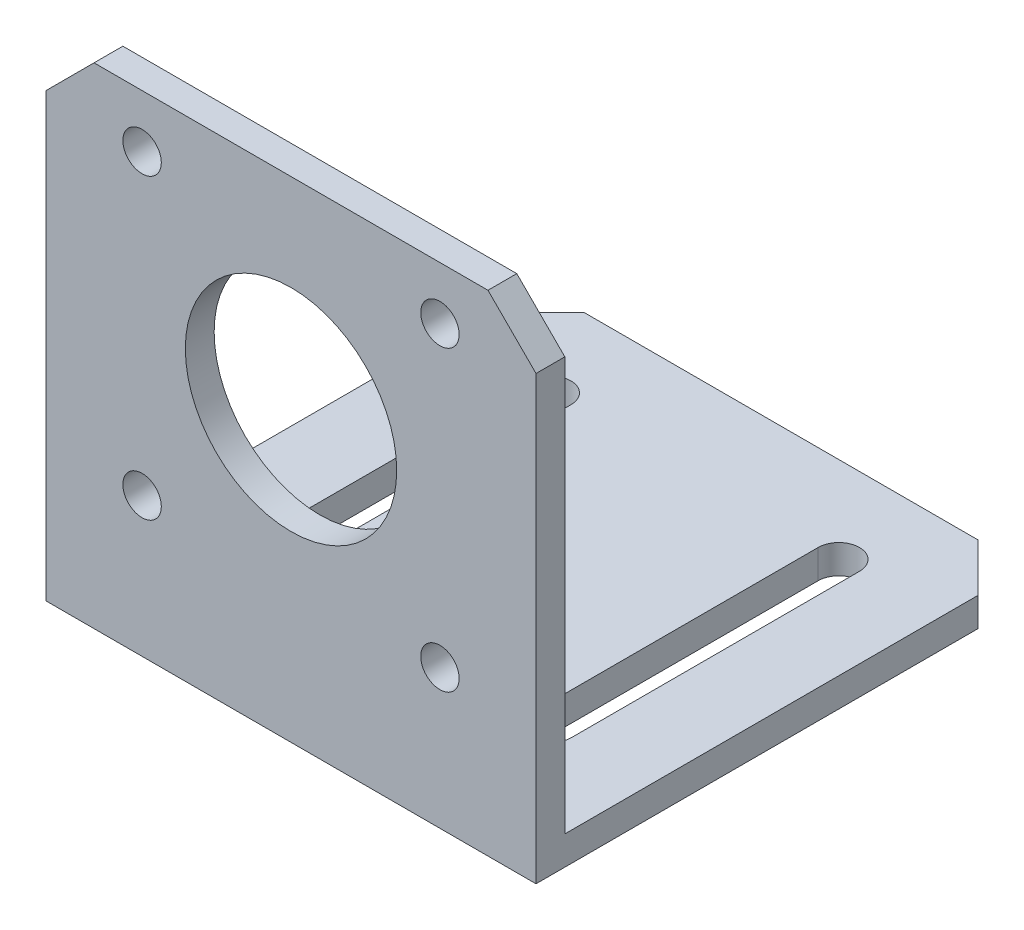
SolidWorks part; units mm, degrees
ref_plane "Ön Düzlem" through (0, 0, 0) normal (0, 0, 1) x (1, 0, 0)
ref_plane "Üst Düzlem" through (0, 0, 0) normal (0, 1, 0) x (1, 0, 0)
ref_plane "Sağ Düzlem" through (0, 0, 0) normal (1, 0, 0) x (0, 0, -1)
sketch "Çizim1" plane through (0, 0, 0) normal (0, 0, 1) x (1, 0, 0)
  line L1 (25.5, -25.5) -> (-25.5, -25.5)
  line L2 (25.5, -25.5) -> (25.5, 25.5)
  line L3 (25.5, 25.5) -> (-25.5, 25.5)
  line L4 (-25.5, -25.5) -> (-25.5, 25.5)
  line L5 (25.5, -25.5) -> (-25.5, 25.5) construction
  line L6 (25.5, 25.5) -> (-25.5, -25.5) construction
  point P0 (0, 0)
  dimension "D1" = 51
  dimension "D2" = 51
extrude "Yükseklik-Ekstrüzyon1" add sketch "Çizim1" along normal blind 51
sketch "Çizim2" plane through (-25.5, 0, 0) normal (-1, 0, 0) x (0, 0, 1)
  line L0 (51, 25.5) -> (51, -25.5) construction
  line L1 (-6.245, 30.9262) -> (48, 30.9262)
  line L2 (-6.245, 30.9262) -> (-6.245, -22.5)
  line L3 (-6.245, -22.5) -> (48, -22.5)
  line L4 (48, 30.9262) -> (48, -22.5)
  line L5 (-6.245, 30.9262) -> (48, -22.5) construction
  line L6 (-6.245, -22.5) -> (48, 30.9262) construction
  line L7 (51, -25.5) -> (0, -25.5) construction
  point P0 (20.8775, 4.2131)
  dimension "D1" = 3
  dimension "D2" = 3
extrude "Kes-Ekstrüzyon1" cut sketch "Çizim2" against normal blind 51
sketch "Çizim3" plane through (0, 0, 51) normal (0, 0, 1) x (1, 0, 0)
  line L0 (25.5, 25.5) -> (-25.5, 25.5) construction
  line L1 (13.432, 4.5) -> (-24.1651, 4.5) construction
  line L2 (0, 20.785) -> (0, -17.5241) construction
  circle A0 centre (0, 4.5) radius 11
  circle A1 centre (-15.5, 20) radius 2
  circle A2 centre (15.5, 20) radius 2
  circle A3 centre (-15.5, -11) radius 2
  circle A4 centre (15.5, -11) radius 2
  dimension "D1" = 22
  dimension "D3" = 4
  dimension "D2" = 21
  dimension "D4" = 31
  dimension "D5" = 31
extrude "Kes-Ekstrüzyon2" cut sketch "Çizim3" against normal blind 51
chamfer "Pah1" distance 5 angle 45 1 edges at (-25.5, 25.5, 49.5)
chamfer "Pah2" distance 5 angle 45 3 edges at (25.5, -24, 0) (-25.5, -24, 0) (25.5, 25.5, 49.5)
sketch "Çizim4" plane through (0, -25.5, 0) normal (0, -1, 0) x (1, 0, 0)
  line L0 (-15.015, 39) -> (-15.015, 9) construction
  line L1 (-12.865, 39) -> (-12.865, 9)
  line L2 (-17.165, 39) -> (-17.165, 9)
  line L3 (0, -2.7893) -> (0, 57.8306) construction
  line L4 (15.015, 39) -> (15.015, 9) construction
  line L5 (12.865, 39) -> (12.865, 9)
  line L6 (17.165, 39) -> (17.165, 9)
  line L7 (-20.5, 0) -> (20.5, 0) construction
  arc A0 (-12.865, 39) -> (-17.165, 39) centre (-15.015, 39) ccw
  arc A1 (-17.165, 9) -> (-12.865, 9) centre (-15.015, 9) ccw
  arc A2 (12.865, 39) -> (17.165, 39) centre (15.015, 39) cw
  arc A3 (17.165, 9) -> (12.865, 9) centre (15.015, 9) cw
  point P2 (-15.015, 24)
  point P12 (15.015, 24)
  dimension "D4" = 9
  dimension "D1" = 30
  dimension "D2" = 4.3
  dimension "D3" = 25.73
extrude "Kes-Ekstrüzyon3" cut sketch "Çizim4" against normal blind 51
